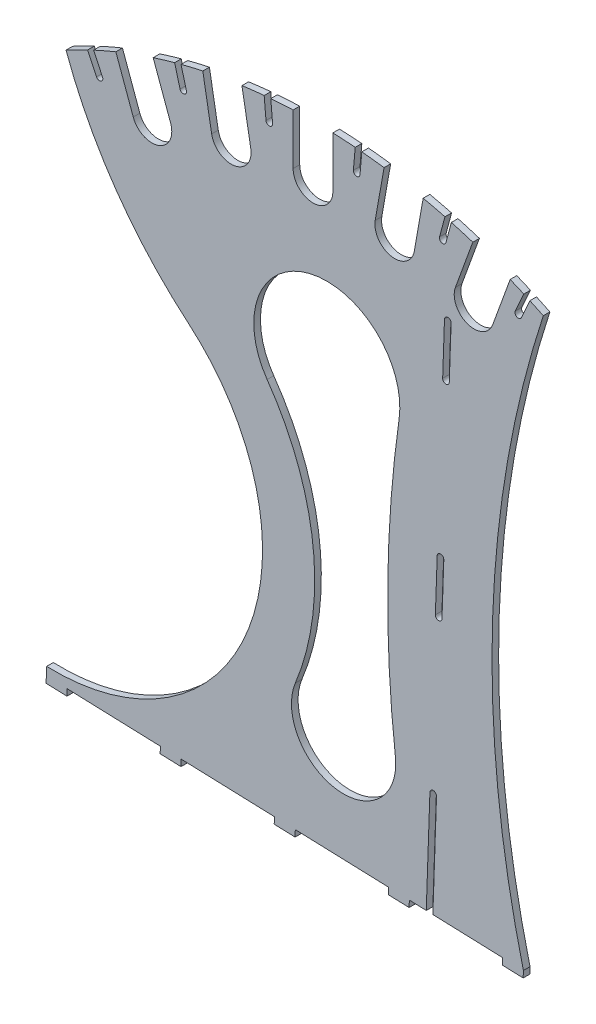
SolidWorks part; units mm, degrees
ref_plane "Front Plane" through (0, 0, 0) normal (0, 0, 1) x (1, 0, 0)
ref_plane "Top Plane" through (0, 0, 0) normal (0, 1, 0) x (1, 0, 0)
ref_plane "Right Plane" through (0, 0, 0) normal (1, 0, 0) x (0, 0, -1)
sketch "Sketch1" plane through (0, 0, 0) normal (0, 0, 1) x (1, 0, 0)
  line L0 (124.6306, 74.9072) -> (-116.031, 83.3183) construction
  line L1 (124.6306, 74.9072) -> (-116.031, 83.3183)
  line L2 (-110.0347, 83.1087) -> (-100.7754, 348.038)
  line L3 (-62.3445, 364.6831) -> (-73.6208, 360.5788) construction
  line L4 (128.3168, 352.1551) -> (118.6343, 75.1167)
  line L5 (-19.854, 374.9856) -> (-31.6717, 372.9018) construction
  line L6 (-67.9827, 362.631) -> (-59.4322, 339.1386) construction
  line L7 (17.78, 377.825) -> (17.78, 127) construction
  line L8 (-59.0321, 365.8887) -> (-50.4816, 342.3964)
  line L9 (-76.9332, 359.3732) -> (-68.3827, 335.8809)
  line L10 (17.78, 127) -> (-59.4322, 339.1386) construction
  line L11 (-25.7628, 373.9437) -> (-21.4216, 349.3235) construction
  line L12 (-16.3825, 375.5977) -> (-12.0413, 350.9775)
  line L13 (-35.1431, 372.2897) -> (-30.8019, 347.6695)
  line L14 (17.78, 377.825) -> (17.78, 352.825) construction
  line L15 (27.305, 377.825) -> (27.305, 352.825)
  line L16 (8.255, 377.825) -> (8.255, 352.825)
  line L17 (103.5427, 362.631) -> (94.9922, 339.1386) construction
  line L18 (94.5921, 365.8887) -> (86.0416, 342.3964)
  line L19 (112.4932, 359.3732) -> (103.9427, 335.8809)
  line L20 (61.3228, 373.9437) -> (56.9816, 349.3235) construction
  line L21 (51.9425, 375.5977) -> (47.6013, 350.9775)
  line L22 (70.7031, 372.2897) -> (66.3619, 347.6695)
  line L23 (-110.0347, 83.1087) -> (-110.1456, 79.9357)
  line L24 (-110.1456, 79.9357) -> (-100.1517, 79.5864)
  line L25 (-100.1517, 79.5864) -> (-100.0408, 82.7594)
  line L26 (-116.1419, 80.1452) -> (124.5197, 71.7341) construction
  line L27 (118.6343, 75.1167) -> (118.5234, 71.9437)
  line L28 (118.5234, 71.9437) -> (108.5295, 72.293)
  line L29 (108.5295, 72.293) -> (108.6404, 75.466)
  line L30 (-55.3659, 81.1981) -> (-55.4768, 78.025)
  line L31 (-55.4768, 78.025) -> (-45.4829, 77.6757)
  line L32 (-45.4829, 77.6757) -> (-45.372, 80.8488)
  line L33 (-0.6971, 79.2874) -> (-0.808, 76.1143)
  line L34 (-0.808, 76.1143) -> (9.1859, 75.765)
  line L35 (9.1859, 75.765) -> (9.2968, 78.9381)
  line L36 (53.9716, 77.3767) -> (53.8607, 74.2036)
  line L37 (53.8607, 74.2036) -> (63.8546, 73.8544)
  line L38 (63.8546, 73.8544) -> (63.9655, 77.0274)
  line L39 (4.2998, 79.1127) -> (4.1889, 75.9397) construction
  line L40 (-100.1517, 79.5864) -> (-0.808, 76.1143) construction
  line L41 (9.1859, 75.765) -> (108.5295, 72.293) construction
  line L42 (73.6618, 76.6885) -> (75.4082, 126.658) construction
  line L43 (72.0752, 76.744) -> (73.8217, 126.7135)
  line L44 (75.2483, 76.6331) -> (76.9947, 126.6026)
  line L45 (78.0278, 201.6123) -> (78.9011, 226.597) construction
  line L46 (76.4413, 201.6677) -> (77.3145, 226.6525)
  line L47 (79.6144, 201.5568) -> (80.4876, 226.5416)
  line L48 (81.5207, 301.5512) -> (82.3939, 326.536) construction
  line L49 (79.9342, 301.6067) -> (80.8074, 326.5914)
  line L50 (83.1072, 301.4958) -> (83.9805, 326.4805)
  arc A0 (128.3168, 352.1551) -> (-100.7754, 348.038) centre (17.78, 127) ccw
  arc A1 (11.78, 377.7532) -> (-19.854, 374.9856) centre (17.78, 127) ccw construction
  arc A2 (-112.7928, 341.1587) -> (-138.8048, 322.9448) centre (17.78, 127) ccw construction
  arc A3 (128.2976, 351.6073) -> (-100.7956, 347.4596) centre (17.78, 127) ccw
  arc A4 (128.0964, 351.7062) -> (-100.5391, 347.5974) centre (17.78, 127) ccw construction
  arc A5 (-59.0321, 365.8887) -> (-76.9332, 359.3732) centre (-67.9827, 362.631) ccw
  arc A6 (-68.3827, 335.8809) -> (-50.4816, 342.3964) centre (-59.4322, 339.1386) ccw
  arc A7 (-16.3825, 375.5977) -> (-35.1431, 372.2897) centre (-25.7628, 373.9437) ccw
  arc A8 (-30.8019, 347.6695) -> (-12.0413, 350.9775) centre (-21.4216, 349.3235) ccw
  arc A9 (27.305, 377.825) -> (8.255, 377.825) centre (17.78, 377.825) ccw
  arc A10 (8.255, 352.825) -> (27.305, 352.825) centre (17.78, 352.825) ccw
  arc A11 (-100.7754, 348.038) -> (-41.8463, 263.4189) centre (87.265, 416.1614) ccw
  arc A12 (-109.8949, 87.1087) -> (-41.8463, 263.4189) centre (-106.402, 187.0477) ccw
  arc A13 (128.3168, 352.1551) -> (118.6343, 75.1167) centre (603.5874, 196.856) ccw
  arc A14 (94.5921, 365.8887) -> (112.4932, 359.3732) centre (103.5427, 362.631) cw
  arc A15 (103.9427, 335.8809) -> (86.0416, 342.3964) centre (94.9922, 339.1386) cw
  arc A16 (51.9425, 375.5977) -> (70.7031, 372.2897) centre (61.3228, 373.9437) cw
  arc A17 (66.3619, 347.6695) -> (47.6013, 350.9775) centre (56.9816, 349.3235) cw
  arc A18 (72.0752, 76.744) -> (75.2483, 76.6331) centre (73.6618, 76.6885) ccw
  arc A19 (76.9947, 126.6026) -> (73.8217, 126.7135) centre (75.4082, 126.658) ccw
  arc A20 (76.4413, 201.6677) -> (79.6144, 201.5568) centre (78.0278, 201.6123) ccw
  arc A21 (80.4876, 226.5416) -> (77.3145, 226.6525) centre (78.9011, 226.597) ccw
  arc A22 (79.9342, 301.6067) -> (83.1072, 301.4958) centre (81.5207, 301.5512) ccw
  arc A23 (83.9805, 326.4805) -> (80.8074, 326.5914) centre (82.3939, 326.536) ccw
  point P3 (-25.7628, 373.9437)
  point P5 (-67.9827, 362.631)
  point P28 (-63.7074, 350.8848)
  point P35 (-23.5922, 361.6336)
  point P41 (17.78, 365.325)
  point P55 (99.2674, 350.8848)
  point P62 (59.1522, 361.6336)
  point P83 (4.2998, 79.1127)
  point P88 (4.1889, 75.9397)
  point P89 (-50.4799, 77.8503)
  point P90 (58.8577, 74.029)
  point P91 (74.535, 101.6733)
  point P98 (78.4644, 214.1046)
  point P107 (81.9573, 314.0436)
  dimension "D8" = 200
  dimension "D9" = 100
  dimension "D11" = 1000
  dimension "D19" = 250.325
  dimension "D1" = 6
  dimension "D2" = 6
  dimension "D4" = 20
  dimension "D5" = 19.05
  dimension "D6" = 25
  dimension "D7" = 10
  dimension "D10" = 4
  dimension "D12" = 10
  dimension "D13" = 3.175
  dimension "D14" = 50
  dimension "D15" = 45
  dimension "D16" = 25
  dimension "D17" = 100
  dimension "D18" = 100
  dimension "D3" = 0.5
extrude "Boss-Extrude1" add sketch "Sketch1" along normal mid plane 3.175
ref_plane "Plane1" through (80, 0, 0) normal (-1, 0, 0) x (0, 0, 1)
ref_plane "Plane2" through (115.8674, -4.0496, 0) normal (0.9994, -0.0349, 0) x (0, 0, -1)
ref_plane "Plane3" through (65.8979, -2.3031, 0) normal (0.9994, -0.0349, 0) x (0, 0, -1)
sketch "Sketch2" plane through (0, 0, 1.5875) normal (0, 0, 1) x (1, 0, 0)
  arc A0 (59.0607, 274.2552) -> (-4.2059, 259.0266) centre (24.409, 279.1806) ccw
  arc A1 (-109.8949, 87.1087) -> (-41.8463, 263.4189) centre (-106.402, 187.0477) ccw construction
  arc A2 (9.3094, 139.7627) -> (57.2837, 133.1992) centre (32.4517, 130.3057) ccw
  arc A3 (9.3094, 139.7627) -> (-4.2059, 259.0266) centre (-106.402, 187.0477) ccw
  arc A5 (59.0607, 274.2552) -> (57.2837, 133.1992) centre (603.5874, 196.856) ccw
  arc A6 (128.1602, 351.6749) -> (118.6343, 75.1167) centre (603.5874, 196.856) ccw construction
  dimension "D1" = 70
  dimension "D2" = 25
  dimension "D3" = 25
  dimension "D4" = 50
extrude "Cut-Extrude1" cut sketch "Sketch2" against normal blind 10
sketch "Sketch3" plane through (0, 0, 1.5875) normal (0, 0, 1) x (1, 0, 0)
  line L0 (-88.8119, 353.4967) -> (-84.5538, 344.4486) construction
  line L1 (-87.3755, 354.1727) -> (-83.1174, 345.1246)
  line L2 (-90.2483, 352.8207) -> (-85.9902, 343.7726)
  line L3 (-47.0089, 368.7954) -> (-44.4207, 359.1361) construction
  line L4 (-45.4755, 369.2063) -> (-42.8873, 359.547)
  line L5 (-48.5423, 368.3845) -> (-45.9541, 358.7252)
  line L6 (-4.0373, 376.3724) -> (-3.1657, 366.4105) construction
  line L7 (-2.4558, 376.5108) -> (-1.5842, 366.5489)
  line L8 (-5.6187, 376.2341) -> (-4.7472, 366.2721)
  line L9 (39.5973, 376.3724) -> (38.7257, 366.4105) construction
  line L10 (41.1787, 376.2341) -> (40.3072, 366.2721)
  line L11 (38.0158, 376.5108) -> (37.1442, 366.5489)
  line L12 (82.5689, 368.7954) -> (79.9807, 359.1361) construction
  line L13 (84.1023, 368.3845) -> (81.5141, 358.7252)
  line L14 (81.0355, 369.2063) -> (78.4473, 359.547)
  line L15 (120.2844, 355.3757) -> (116.1896, 346.2525) construction
  line L16 (121.7327, 354.7256) -> (117.6379, 345.6025)
  line L17 (118.8361, 356.0257) -> (114.7412, 346.9026)
  arc A0 (-76.7248, 358.8005) -> (-100.6027, 347.5632) centre (17.78, 127) ccw construction
  arc A1 (-87.3755, 354.1727) -> (-90.2483, 352.8207) centre (-88.8119, 353.4967) ccw
  arc A2 (-85.9902, 343.7726) -> (-83.1174, 345.1246) centre (-84.5538, 344.4486) ccw
  arc A3 (-35.0373, 371.6895) -> (-58.8236, 365.3159) centre (17.78, 127) ccw construction
  arc A4 (-45.4755, 369.2063) -> (-48.5423, 368.3845) centre (-47.0089, 368.7954) ccw
  arc A5 (-45.9541, 358.7252) -> (-42.8873, 359.547) centre (-44.4207, 359.1361) ccw
  arc A6 (8.255, 377.1437) -> (-16.2767, 374.9975) centre (17.78, 127) ccw construction
  arc A7 (-2.4558, 376.5108) -> (-5.6187, 376.2341) centre (-4.0373, 376.3724) ccw
  arc A8 (-4.7472, 366.2721) -> (-1.5842, 366.5489) centre (-3.1657, 366.4105) ccw
  arc A9 (51.8367, 374.9975) -> (27.305, 377.1437) centre (17.78, 127) ccw construction
  arc A10 (41.1787, 376.2341) -> (38.0158, 376.5108) centre (39.5973, 376.3724) ccw
  arc A11 (37.1442, 366.5489) -> (40.3072, 366.2721) centre (38.7257, 366.4105) ccw
  arc A12 (94.3836, 365.3159) -> (70.5973, 371.6895) centre (17.78, 127) ccw construction
  arc A13 (84.1023, 368.3845) -> (81.0355, 369.2063) centre (82.5689, 368.7954) ccw
  arc A14 (78.4473, 359.547) -> (81.5141, 358.7252) centre (79.9807, 359.1361) ccw
  arc A15 (128.1602, 351.6749) -> (112.2848, 358.8005) centre (17.78, 127) ccw construction
  arc A16 (121.7327, 354.7256) -> (118.8361, 356.0257) centre (120.2844, 355.3757) ccw
  arc A17 (114.7412, 346.9026) -> (117.6379, 345.6025) centre (116.1896, 346.2525) ccw
  point P5 (-86.6829, 348.9727)
  point P10 (-45.7148, 363.9658)
  point P20 (-3.6015, 371.3915)
  point P30 (39.1615, 371.3915)
  point P40 (81.2748, 363.9658)
  point P50 (118.237, 350.8141)
  point P61 (17.78, 127)
  dimension "D1" = 3.175
  dimension "D2" = 10
extrude "Cut-Extrude2" cut sketch "Sketch3" against normal through all
